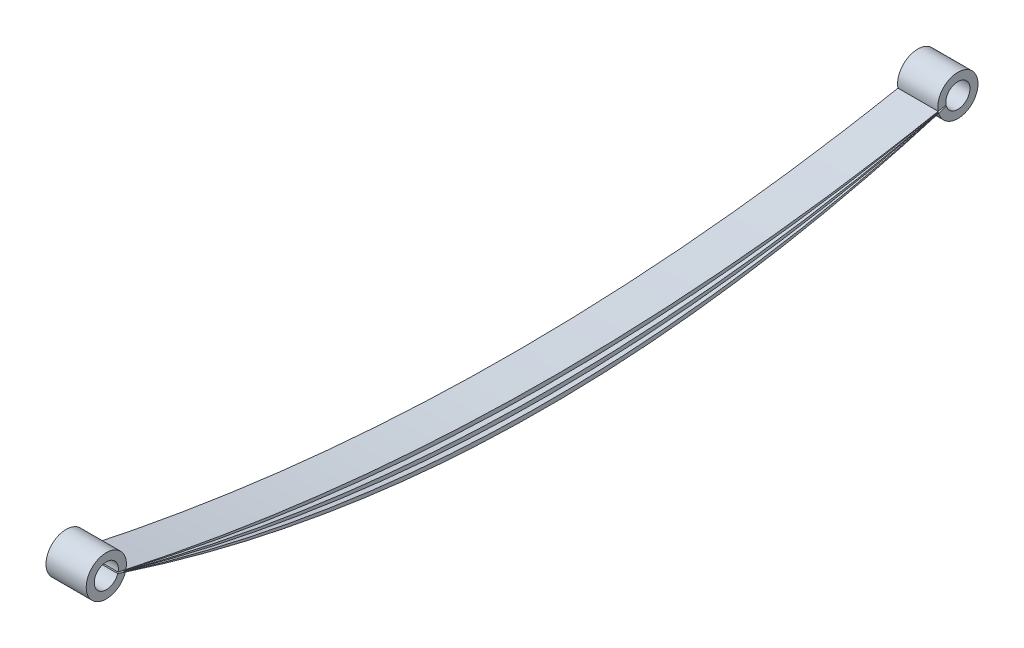
SolidWorks part; units mm, degrees
ref_plane "Front Plane" through (0, 0, 0) normal (0, 0, 1) x (1, 0, 0)
ref_plane "Top Plane" through (0, 0, 0) normal (0, 1, 0) x (1, 0, 0)
ref_plane "Right Plane" through (0, 0, 0) normal (1, 0, 0) x (0, 0, -1)
sketch "Sketch1" plane through (0, 0, 0) normal (1, 0, 0) x (0, 0, -1)
  circle A0 centre (-40.5629, 43.976) radius 2.5
  circle A1 centre (65.3271, 42.7574) radius 2.5
  spline S0 degree 2 poles (-40.5629, 43.976) (12.2818, 31.9782) (65.3271, 42.7574) knots 0 0 0 1 1 1
  spline S1 degree 2 poles (-40.5629, 43.976) (12.2758, 30.9358) (65.3271, 42.7574) knots 0 0 0 1 1 1
  spline S2 degree 2 poles (-40.5629, 43.976) (12.2687, 29.5578) (65.3271, 42.7574) knots 0 0 0 1 1 1
  spline S3 degree 2 poles (-40.5629, 43.976) (12.2638, 28.4994) (65.3271, 42.7574) knots 0 0 0 1 1 1
  spline S4 degree 2 poles (-40.5629, 43.976) (12.1191, 27.2249) (65.3271, 42.7574) knots 0 0 0 1 1 1
  spline S5 degree 2 poles (-40.5629, 43.976) (12.0964, 26.1373) (65.3271, 42.7574) knots 0 0 0 1 1 1
  point P4 (0, 0)
  point P7 (0, 0)
  point P8 (10.5883, 32.8792)
  point P9 (0, 0)
  point P13 (13.6614, 37.1399)
  point P14 (13.6614, 36.4513)
  point P16 (13.6614, 35.9224)
  point P17 (10.5883, 35.3229)
  point P18 (10.5883, 34.7794)
  dimension "D2" = 5
  dimension "D1" = 105.89
extrude "Boss-Extrude1" add sketch "Sketch1" along normal blind 5 contours A0 S1 A1 S0 | A0 S3 A1 S2 | A0 S5 A1 S4 | S5 S0 A0 | S5 A1 S0
sketch "Sketch2" plane through (0, 0, 0) normal (-1, 0, 0) x (0, 0, 1)
  circle A10 centre (-65.3271, 42.7574) radius 1.5
  dimension "D1" = 3
extrude "Cut-Extrude1" cut sketch "Sketch2" against normal blind 5
sketch "Sketch3" plane through (0, 0, 0) normal (-1, 0, 0) x (0, 0, 1)
  circle A0 centre (40.5629, 43.976) radius 1.5
  dimension "D1" = 3
extrude "Cut-Extrude2" cut sketch "Sketch3" against normal blind 5
